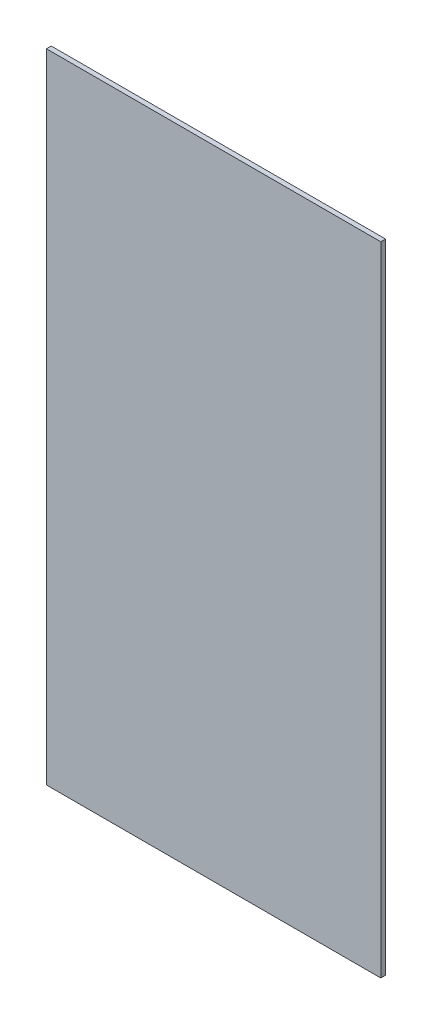
SolidWorks part; units mm, degrees
ref_plane "Спереди" through (0, 0, 0) normal (0, 0, 1) x (1, 0, 0)
ref_plane "Сверху" through (0, 0, 0) normal (0, 1, 0) x (1, 0, 0)
ref_plane "Справа" through (0, 0, 0) normal (1, 0, 0) x (0, 0, -1)
sketch "Эскиз1" plane through (0, 0, 0) normal (0, 1, 0) x (1, 0, 0)
  line L1 (-144.7882, -2.3414) -> (134.7883, -2.3414)
  line L2 (-144.7882, -2.3414) -> (-144.7882, -6.3414)
  line L3 (-144.7882, -6.3414) -> (134.7883, -6.3414)
  line L4 (134.7883, -2.3414) -> (134.7883, -6.3414)
extrude "Вытянуть1" add sketch "Эскиз1" along normal up to surface (533.2137 mm away)
sketch "Эскиз2" plane through (0, 0, 2.3414) normal (0, 0, -1) x (-1, 0, 0)
  line L1 (13.9114, 91.345) -> (63.9114, 91.345)
  line L2 (13.9114, 91.345) -> (13.9114, 41.345)
  line L3 (13.9114, 41.345) -> (63.9114, 41.345)
  line L4 (63.9114, 91.345) -> (63.9114, 41.345)
extrude "Вырез-Вытянуть1" cut sketch "Эскиз2" against normal blind 3
sketch "Эскиз3" plane through (0, 0, 6.3414) normal (0, 0, 1) x (1, 0, 0)
  line L0 (-5, 538.7137) -> (-5, 708.1849) construction
  line L3 (-63.8147, 436.4018) -> (53.8148, 436.4018)
  line L4 (-73.8147, 426.4018) -> (-73.8147, 148.4471)
  line L5 (-63.8147, 138.4471) -> (53.8148, 138.4471)
  line L6 (63.8148, 426.4018) -> (63.8148, 148.4471)
  arc A0 (-73.8147, 426.4018) -> (-63.8147, 436.4018) centre (-63.8147, 426.4018) cw
  arc A1 (63.8148, 426.4018) -> (53.8148, 436.4018) centre (53.8148, 426.4018) ccw
  arc A2 (53.8148, 138.4471) -> (63.8148, 148.4471) centre (53.8148, 148.4471) ccw
  arc A3 (-73.8147, 148.4471) -> (-63.8147, 138.4471) centre (-63.8147, 148.4471) ccw
  dimension "D1" = 10
